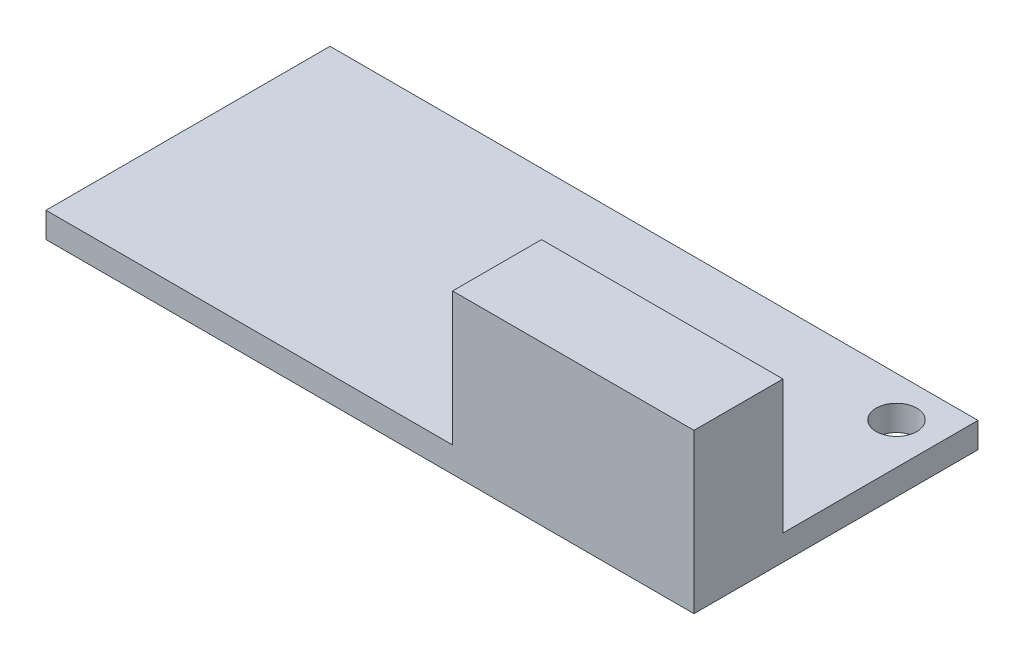
SolidWorks part; units mm, degrees
ref_plane "Front Plane" through (0, 0, 0) normal (0, 0, 1) x (1, 0, 0)
ref_plane "Top Plane" through (0, 0, 0) normal (0, 1, 0) x (1, 0, 0)
ref_plane "Right Plane" through (0, 0, 0) normal (1, 0, 0) x (0, 0, -1)
sketch "Sketch1" plane through (0, 0, 0) normal (0, 1, 0) x (1, 0, 0)
  line L1 (-25.5, -11.176) -> (25.5, -11.176)
  line L2 (-25.5, -11.176) -> (-25.5, 11.176)
  line L3 (-25.5, 11.176) -> (25.5, 11.176)
  line L4 (25.5, -11.176) -> (25.5, 11.176)
  line L5 (-25.5, -11.176) -> (25.5, 11.176) construction
  line L6 (-25.5, 11.176) -> (25.5, -11.176) construction
  circle A0 centre (22.252, 8.0056) radius 1.6
  point P0 (0, 0)
  dimension "D3" = 3.2
  dimension "D1" = 51
  dimension "D2" = 22.352
  dimension "D4" = 47.752
extrude "Boss-Extrude1" add sketch "Sketch1" along normal blind 2
sketch "Sketch2" plane through (0, 2, 0) normal (0, 1, 0) x (1, 0, 0)
  line L1 (25.5, -11.176) -> (6.5, -11.176)
  line L2 (25.5, -11.176) -> (25.5, -4.176)
  line L3 (25.5, -4.176) -> (6.5, -4.176)
  line L4 (6.5, -11.176) -> (6.5, -4.176)
  dimension "D1" = 7
  dimension "D2" = 19
extrude "Boss-Extrude2" add sketch "Sketch2" along normal blind 10.5
sketch "Sketch3" plane through (0, 0, 0) normal (0, -1, 0) x (1, 0, 0)
  line L1 (-25.5, -11.176) -> (17.68, -11.176)
  line L2 (-25.5, -11.176) -> (-25.5, -3.556)
  line L3 (-25.5, -3.556) -> (17.68, -3.556)
  line L4 (17.68, -11.176) -> (17.68, -3.556)
  dimension "D1" = 7.62
  dimension "D2" = 43.18
extrude "Boss-Extrude3" add sketch "Sketch3" along normal blind 4.5
